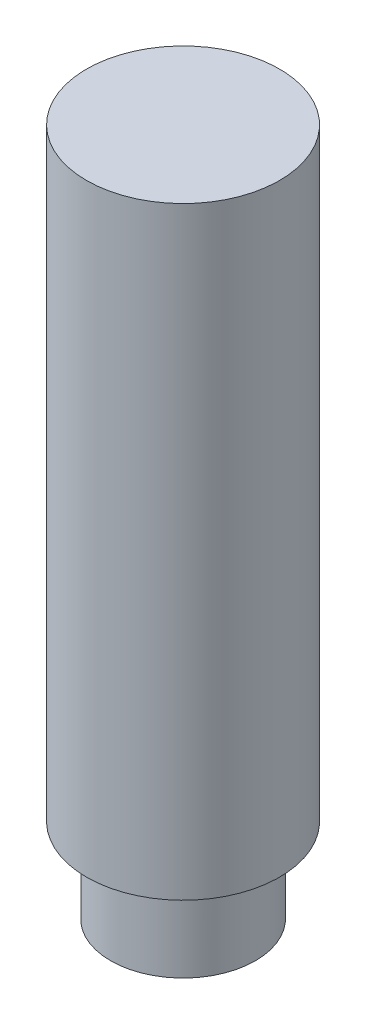
SolidWorks part; units mm, degrees
ref_plane "Спереди" through (0, 0, 0) normal (0, 0, 1) x (1, 0, 0)
ref_plane "Сверху" through (0, 0, 0) normal (0, 1, 0) x (1, 0, 0)
ref_plane "Справа" through (0, 0, 0) normal (1, 0, 0) x (0, 0, -1)
sketch "Эскиз1" plane through (0, 0, 0) normal (0, 1, 0) x (1, 0, 0)
  circle A0 centre (0, 0) radius 4
  dimension "D1" = 8
extrude "Бобышка-Вытянуть1" add sketch "Эскиз1" along normal blind 25
sketch "Эскиз2" plane through (0, 0, 0) normal (0, -1, 0) x (1, 0, 0)
  circle A0 centre (0, 0) radius 3
  dimension "D1" = 6
extrude "Бобышка-Вытянуть2" add sketch "Эскиз2" along normal blind 3.5
